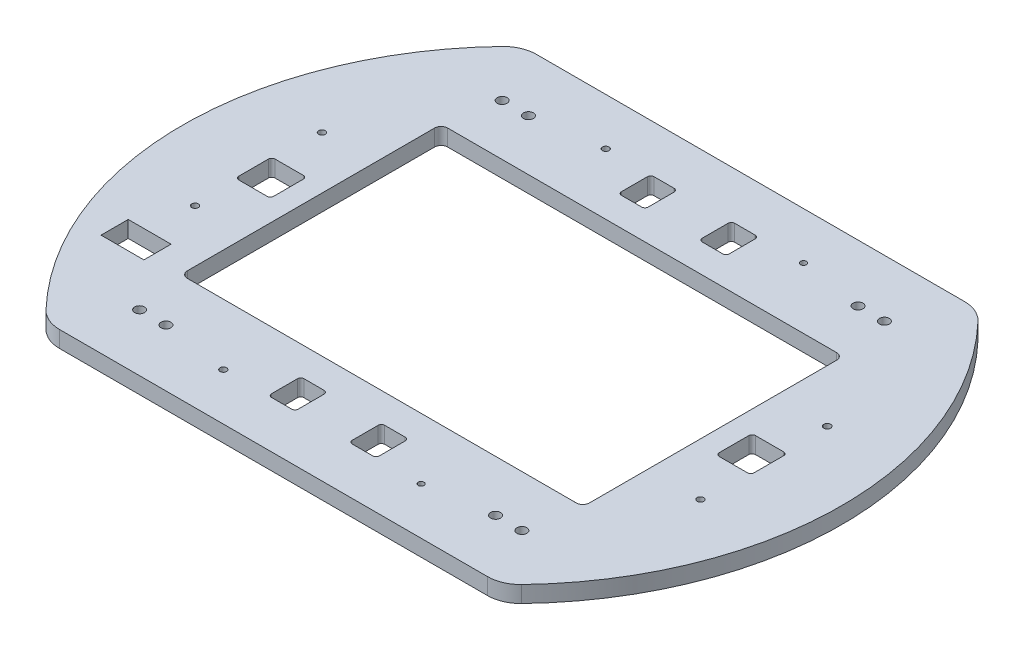
SolidWorks part; units mm, degrees
ref_plane "Plano frontal" through (0, 0, 0) normal (0, 0, 1) x (1, 0, 0)
ref_plane "Plano superior" through (0, 0, 0) normal (0, 1, 0) x (1, 0, 0)
ref_plane "Plano direito" through (0, 0, 0) normal (1, 0, 0) x (0, 0, -1)
sketch "Esboço1" plane through (0, 0, 0) normal (0, 1, 0) x (1, 0, 0)
  line L0 (0, 0) -> (0, 303.4641) construction
  line L1 (-180.7753, 0) -> (210.2784, 0) construction
  line L2 (-69.0624, -72.3214) -> (69.0624, -72.3214)
  line L3 (-69.0624, 72.3214) -> (69.0624, 72.3214)
  circle A0 centre (0, 0) radius 100
  circle A1 centre (0, 260) radius 200
  circle A2 centre (0, -260) radius 200
  circle A3 centre (0, 0) radius 9.3273 construction
  point P6 (0, 60)
  point P7 (0, 100)
  dimension "D1" = 200
  dimension "D2" = 400
  dimension "D3" = 40
extrude "Ressalto-extrusão1" add sketch "Esboço1" along normal blind 5 contours A0 A2 A1 | A2 A0 L2 | A0 A1 L3
fillet "Filete1" radius 10 4 edges at (69.0624, 2.5, 72.3214) (-69.0624, 2.5, 72.3214) (-69.0624, 2.5, -72.3214) (69.0624, 2.5, -72.3214)
sketch "Esboço4" plane through (0, 5, 0) normal (0, 1, 0) x (1, 0, 0)
  line L0 (0, 72.3214) -> (0, -72.3214) construction
  line L1 (-100, 0) -> (100, 0) construction
  line L3 (-64.9311, 72.3214) -> (64.9311, 72.3214) construction
  line L4 (-64.9311, -72.3214) -> (64.9311, -72.3214) construction
  circle A0 centre (-50, 55) radius 1.5
  arc A1 (-72.1456, 69.246) -> (-72.1456, -69.246) centre (0, 0) ccw construction
  arc A2 (72.1456, -69.246) -> (72.1456, 69.246) centre (0, 0) ccw construction
  dimension "D1" = 3
  dimension "D2" = 55
extrude "Corte-extrusão3" cut sketch "Esboço4" against normal through all
mirror "Espelhar3" about plane through (0, 0, 0) normal (1, 0, 0) of "Corte-extrusão3"
mirror "Espelhar4" about plane through (0, 0, 0) normal (0, 0, 1) of "Espelhar3", "Corte-extrusão3"
sketch "Sketch1" plane through (0, 5, 0) normal (0, 1, 0) x (1, 0, 0)
  line L0 (0, 72.3214) -> (0, -72.3214) construction
  line L1 (-64.9311, 72.3214) -> (64.9311, 72.3214) construction
  line L2 (61, -39.5) -> (-61, -39.5)
  line L3 (61, -39.5) -> (61, 39.5)
  line L4 (61, 39.5) -> (-61, 39.5)
  line L5 (-61, -39.5) -> (-61, 39.5)
  line L6 (61, -39.5) -> (-61, 39.5) construction
  line L7 (61, 39.5) -> (-61, -39.5) construction
  line L8 (-64.9311, -72.3214) -> (64.9311, -72.3214) construction
  point P9 (0, 0)
  dimension "D1" = 122
  dimension "D2" = 79
extrude "Cut-Extrude1" cut sketch "Sketch1" against normal through all
fillet "Fillet2" radius 2 4 edges at (61, 2.5, -39.5) (61, 2.5, 39.5) (-61, 2.5, 39.5) (-61, 2.5, -39.5)
sketch "Esboço5" plane through (0, 5, 0) normal (0, 1, 0) x (1, 0, 0)
  line L1 (-100, 0) -> (100, 0) construction
  arc A2 (-72.1456, 69.246) -> (-72.1456, -69.246) centre (0, 0) ccw construction
  arc A3 (72.1456, -69.246) -> (72.1456, 69.246) centre (0, 0) ccw construction
sketch "Esboço6" plane through (0, 5, 0) normal (0, 1, 0) x (1, 0, 0)
  circle A0 centre (-76.9204, 19.2361) radius 1
  circle A1 centre (-76.9204, -19.2381) radius 1
extrude "Corte-extrusão4" cut sketch "Esboço6" against normal through all
sketch "Esboço8" plane through (0, 5, 0) normal (0, 1, 0) x (1, 0, 0)
  line L1 (77.0588, -5.618) -> (68.4788, -5.618)
  line L2 (78.0588, -4.618) -> (78.0588, 4.382)
  line L3 (77.0588, 5.382) -> (68.4788, 5.382)
  line L4 (67.4788, -4.618) -> (67.4788, 4.382)
  circle A0 centre (76.9204, -19.7562) radius 1
  circle A1 centre (76.9204, 18.7181) radius 1.0425
  arc A2 (68.4788, -5.618) -> (67.4788, -4.618) centre (68.4788, -4.618) cw
  arc A3 (77.0588, -5.618) -> (78.0588, -4.618) centre (77.0588, -4.618) ccw
  arc A4 (78.0588, 4.382) -> (77.0588, 5.382) centre (77.0588, 4.382) ccw
  arc A5 (67.4788, 4.382) -> (68.4788, 5.382) centre (68.4788, 4.382) cw
  dimension "D1" = 1
extrude "Corte-extrusão5" cut sketch "Esboço8" against normal through all
ref_plane "Plano1" through (-76.8071, -55.6914, 35.0032) normal (0.5446, 0, 0.8387) x (0.8387, 0, -0.5446)
sketch "Esboço12" plane through (0, 5, 0) normal (0, 1, 0) x (1, 0, 0)
  line L1 (-83.4589, -32.9829) -> (-70.4589, -32.9829)
  line L2 (-83.4589, -32.9829) -> (-83.4589, -41.2329)
  line L3 (-83.4589, -41.2329) -> (-70.4589, -41.2329)
  line L4 (-70.4589, -32.9829) -> (-70.4589, -41.2329)
  line L5 (-77.0588, 5.1605) -> (-68.4788, 5.1605)
  line L6 (-78.0588, 4.1605) -> (-78.0588, -4.8395)
  line L7 (-77.0588, -5.8395) -> (-68.4788, -5.8395)
  line L8 (-67.4788, 4.1605) -> (-67.4788, -4.8395)
  arc A0 (-78.0588, -4.8395) -> (-77.0588, -5.8395) centre (-77.0588, -4.8395) ccw
  arc A1 (-68.4788, -5.8395) -> (-67.4788, -4.8395) centre (-68.4788, -4.8395) ccw
  arc A2 (-68.4788, 5.1605) -> (-67.4788, 4.1605) centre (-68.4788, 4.1605) cw
  arc A3 (-77.0588, 5.1605) -> (-78.0588, 4.1605) centre (-77.0588, 4.1605) ccw
  dimension "D3" = 1
  dimension "D1" = 8.25
  dimension "D2" = 13
extrude "Corte-extrusão7" cut sketch "Esboço12" against normal through all
sketch "Esboço13" plane through (0, 5, 0) normal (0, 1, 0) x (1, 0, 0)
  line L0 (0, 72.3214) -> (0, -72.3214) construction
  line L1 (-64.9311, 72.3214) -> (64.9311, 72.3214) construction
  line L2 (-64.9311, -72.3214) -> (64.9311, -72.3214) construction
  line L3 (-100, 0) -> (100, 0) construction
  circle A0 centre (-58, -55) radius 1.5
  arc A1 (-72.1456, 69.246) -> (-72.1456, -69.246) centre (0, 0) ccw construction
  arc A2 (72.1456, -69.246) -> (72.1456, 69.246) centre (0, 0) ccw construction
  circle A3 centre (58, -55) radius 1.5
  circle A4 centre (58, 55) radius 1.5
  circle A5 centre (-58, 55) radius 1.5
  circle A6 centre (-50, -55) radius 1.5 construction
  dimension "D1" = 8
extrude "Corte-extrusão8" cut sketch "Esboço13" against normal through all
sketch "Esboço14" plane through (0, 5, 0) normal (0, 1, 0) x (1, 0, 0)
  line L1 (-14.9306, -48.1702) -> (-8.8302, -48.1702)
  line L2 (-15.9306, -49.1702) -> (-15.9306, -57.0183)
  line L3 (-14.9306, -58.0183) -> (-8.8302, -58.0183)
  line L4 (-7.8302, -49.1702) -> (-7.8302, -57.0183)
  line L5 (9.5467, -48.1702) -> (15.7645, -48.1702)
  line L6 (8.5467, -49.1702) -> (8.5467, -57.0183)
  line L7 (9.5467, -58.0183) -> (15.7645, -58.0183)
  line L8 (16.7645, -49.1702) -> (16.7645, -57.0183)
  circle A0 centre (-29.5707, -58.0183) radius 1
  circle A1 centre (30.4293, -58.0183) radius 0.8859
  arc A2 (8.5467, -57.0183) -> (9.5467, -58.0183) centre (9.5467, -57.0183) ccw
  arc A3 (15.7645, -58.0183) -> (16.7645, -57.0183) centre (15.7645, -57.0183) ccw
  arc A4 (15.7645, -48.1702) -> (16.7645, -49.1702) centre (15.7645, -49.1702) cw
  arc A5 (9.5467, -48.1702) -> (8.5467, -49.1702) centre (9.5467, -49.1702) ccw
  arc A6 (-15.9306, -57.0183) -> (-14.9306, -58.0183) centre (-14.9306, -57.0183) ccw
  arc A7 (-8.8302, -58.0183) -> (-7.8302, -57.0183) centre (-8.8302, -57.0183) ccw
  arc A8 (-8.8302, -48.1702) -> (-7.8302, -49.1702) centre (-8.8302, -49.1702) cw
  arc A9 (-14.9306, -48.1702) -> (-15.9306, -49.1702) centre (-14.9306, -49.1702) ccw
  dimension "D1" = 1
extrude "Corte-extrusão9" cut sketch "Esboço14" against normal through all
mirror "Espelhar5" about plane through (0, 0, 0) normal (0, 0, 1) of "Corte-extrusão9"
